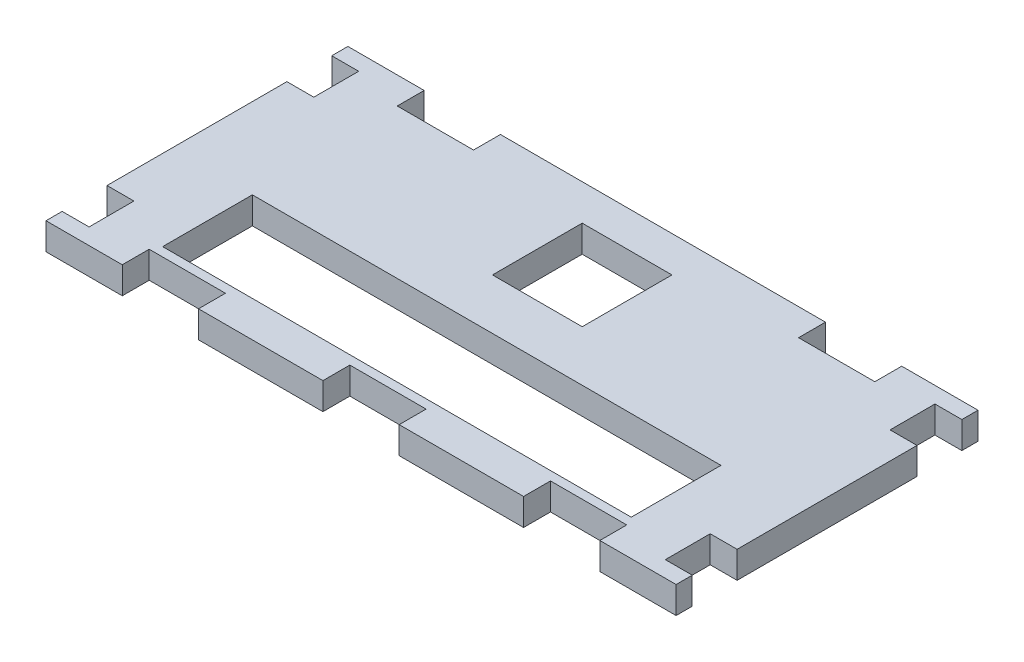
SolidWorks part; units mm, degrees
material "Balsa"
ref_plane "Alzado" through (0, 0, 0) normal (0, 0, 1) x (1, 0, 0)
ref_plane "Planta" through (0, 0, 0) normal (0, 1, 0) x (1, 0, 0)
ref_plane "Vista lateral" through (0, 0, 0) normal (1, 0, 0) x (0, 0, -1)
sketch "Croquis1" plane through (0, 0, 0) normal (0, 1, 0) x (1, 0, 0)
  line L0 (17, 33.65) -> (30.865, 33.65)
  line L1 (0, 0) -> (8.5, 0)
  line L2 (0, 0) -> (0, 1.8)
  line L3 (0, 33.65) -> (8.5, 33.65)
  line L4 (70.23, 0) -> (70.23, 1.8)
  line L6 (8.5, 33.65) -> (8.5, 30.65)
  line L7 (8.5, 30.65) -> (17, 30.65)
  line L8 (17, 33.65) -> (17, 30.65)
  line L14 (53.23, 33.65) -> (53.23, 30.65)
  line L15 (53.23, 30.65) -> (61.73, 30.65)
  line L16 (61.73, 33.65) -> (61.73, 30.65)
  line L18 (8.5, 0) -> (8.5, 3)
  line L19 (8.5, 3) -> (17, 3)
  line L20 (17, 0) -> (17, 3)
  line L22 (30.865, 0) -> (30.865, 3)
  line L23 (30.865, 3) -> (39.365, 3)
  line L24 (39.365, 0) -> (39.365, 3)
  line L26 (53.23, 0) -> (53.23, 3)
  line L27 (53.23, 3) -> (61.73, 3)
  line L28 (61.73, 0) -> (61.73, 3)
  line L29 (39.365, 33.65) -> (53.23, 33.65)
  line L30 (61.73, 33.65) -> (70.23, 33.65)
  line L31 (17, 0) -> (30.865, 0)
  line L32 (39.365, 0) -> (53.23, 0)
  line L33 (61.73, 0) -> (70.23, 0)
  line L34 (0, 31.85) -> (0, 33.65)
  line L35 (0, 31.85) -> (3, 31.85)
  line L37 (0, 26.85) -> (3, 26.85)
  line L38 (3, 31.85) -> (3, 26.85)
  line L39 (0, 1.8) -> (3, 1.8)
  line L41 (0, 6.8) -> (3, 6.8)
  line L42 (3, 1.8) -> (3, 6.8)
  line L43 (70.23, 31.85) -> (67.23, 31.85)
  line L45 (70.23, 26.85) -> (67.23, 26.85)
  line L46 (67.23, 31.85) -> (67.23, 26.85)
  line L47 (70.23, 6.8) -> (67.23, 6.8)
  line L49 (70.23, 1.8) -> (67.23, 1.8)
  line L50 (67.23, 6.8) -> (67.23, 1.8)
  line L51 (0, 6.8) -> (0, 26.85)
  line L52 (70.23, 31.85) -> (70.23, 33.65)
  line L53 (70.23, 6.8) -> (70.23, 26.85)
  line L54 (30.865, 33.65) -> (39.365, 33.65)
  line L56 (4, 29.65) -> (66.23, 29.65)
  line L57 (4, 29.65) -> (4, 4)
  line L58 (4, 4) -> (66.23, 4)
  line L59 (66.23, 29.65) -> (66.23, 4)
  line L60 (9, 4) -> (61.23, 4)
  line L61 (9, 4) -> (9, 14)
  line L62 (9, 14) -> (61.23, 14)
  line L63 (61.23, 4) -> (61.23, 14)
  line L64 (35.115, 19.65) -> (35.115, 4) construction
  line L65 (30.115, 19.65) -> (40.115, 19.65)
  line L66 (30.115, 19.65) -> (30.115, 29.65)
  line L67 (30.115, 29.65) -> (40.115, 29.65)
  line L68 (40.115, 19.65) -> (40.115, 29.65)
  circle A0 centre (7.3, 26.35) radius 1.3
  circle A1 centre (7.3, 7.3) radius 1.3
  circle A2 centre (62.93, 26.35) radius 1.3
  circle A3 centre (62.93, 7.3) radius 1.3
  point P61 (35.115, 24.65)
  dimension "D3" = 2.6
  dimension "D1" = 70.23
  dimension "D2" = 33.65
  dimension "D4" = 7.3
  dimension "D5" = 7.3
  dimension "D6" = 7.3
  dimension "D7" = 7.3
  dimension "D8" = 8.5
  dimension "D9" = 3
  dimension "D10" = 8.5
  dimension "D11" = 8.5
  dimension "D12" = 8.5
  dimension "D13" = 8.5
  dimension "D14" = 3
  dimension "D15" = 3
  dimension "D16" = 5
  dimension "D17" = 5
  dimension "D18" = 5
  dimension "D19" = 3
  dimension "D20" = 5
  dimension "D21" = 3
  dimension "D22" = 1.8
  dimension "D23" = 1.8
  dimension "D24" = 8.5
  dimension "D25" = 8.5
  dimension "D26" = 13.865
  dimension "D27" = 13.865
  dimension "D28" = 8.5
  dimension "D29" = 4
  dimension "D30" = 4
  dimension "D31" = 4
  dimension "D32" = 4
  dimension "D33" = 5
  dimension "D34" = 5
  dimension "D35" = 10
  dimension "D36" = 10
  dimension "D37" = 10
extrude "Saliente-Extruir1" add sketch "Croquis1" along normal blind 3 contours L54 L0 L8 L7 L6 L3 L34 L35 L38 L37 L51 L41 L42 L39 L2 L1 L18 L19 L20 L31 L22 L23 L24 L32 L26 L27 L28 L33 L4 L49 L50 L47 L53 L45 L46 L43 L52 L30 L16 L15 L14 L29 L56 L59 L58 L60 | L64 L65 L66 L56 L57 L58 L61 L62 A1 A0 | L65 L64 L62 L63 L58 L59 L56 L68 A2 A3 | A1 | A0 | A2 | A3
